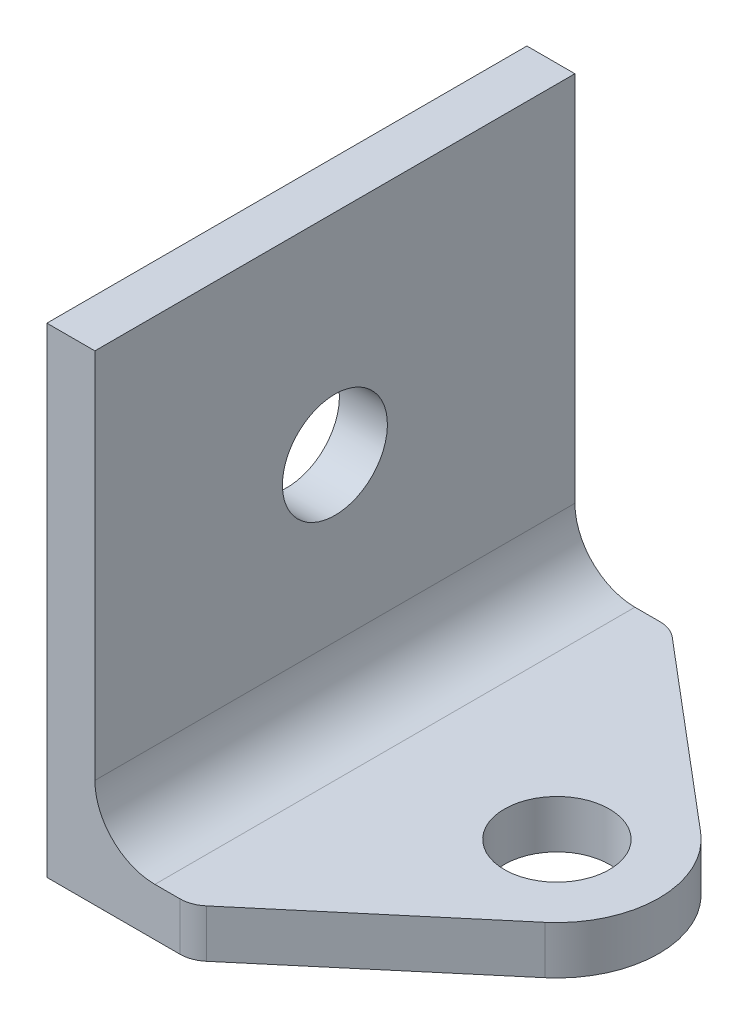
SolidWorks part; units mm, degrees
material "6061-T6 (SS)"
ref_plane "Ebene vorne" through (0, 0, 0) normal (0, 0, 1) x (1, 0, 0)
ref_plane "Ebene oben" through (0, 0, 0) normal (0, 1, 0) x (1, 0, 0)
ref_plane "Ebene rechts" through (0, 0, 0) normal (1, 0, 0) x (0, 0, -1)
sketch "Skizze1" plane through (0, 0, 0) normal (0, 0, 1) x (1, 0, 0)
  line L0 (0, 0) -> (80, 0)
  line L1 (80, 0) -> (80, 8)
  line L2 (80, 8) -> (18, 8)
  line L3 (8, 18) -> (8, 80)
  line L4 (8, 80) -> (0, 80)
  line L5 (0, 80) -> (0, 0)
  arc A0 (18, 8) -> (8, 18) centre (18, 18) cw
  dimension "D5" = 10
  dimension "D1" = 8
  dimension "D2" = 8
  dimension "D3" = 80
  dimension "D4" = 80
extrude "Aufsatz Auftragen Main Body" add sketch "Skizze1" along normal mid plane 80
sketch "Skizze3" plane through (0, 8, 0) normal (0, 1, 0) x (1, 0, 0)
  line L0 (0, -40) -> (0, 40) construction
  circle A0 centre (45, 0) radius 8.75
  dimension "D1" = 17.5
  dimension "D2" = 45
extrude "Bohrung Horizontal" cut sketch "Skizze3" against normal through all
sketch "Skizze4" plane through (8, 0, 0) normal (1, 0, 0) x (0, 0, -1)
  line L1 (-40, 0) -> (40, 0) construction
  circle A0 centre (0, 45) radius 8.75
  dimension "D1" = 17.5
  dimension "D2" = 45
other "AusrichtungGruppe1"
extrude "Bohrung Vertikal" cut sketch "Skizze4" against normal through all
sketch "Skizze5" plane through (0, 8, 0) normal (0, 1, 0) x (1, 0, 0)
  line L0 (24, -40) -> (55.9719, -12.9853)
  line L1 (80, -40) -> (18, -40) construction
  line L2 (24, 40) -> (55.9719, 12.9853)
  line L3 (80, 40) -> (18, 40) construction
  line L4 (18, -40) -> (18, 40) construction
  line L5 (24, 40) -> (80, 40)
  line L6 (80, 40) -> (80, -40)
  line L7 (80, -40) -> (24, -40)
  arc A0 (55.9719, -12.9853) -> (55.9719, 12.9853) centre (45, 0) ccw
  circle A1 centre (45, 0) radius 8.75 construction
  dimension "D1" = 34
  dimension "D2" = 6
  dimension "D3" = 6
extrude "Linear Austragen" cut sketch "Skizze5" against normal through all
fillet "Verrundung" radius 5 2 edges at (24, 4, -40) (24, 4, 40)
